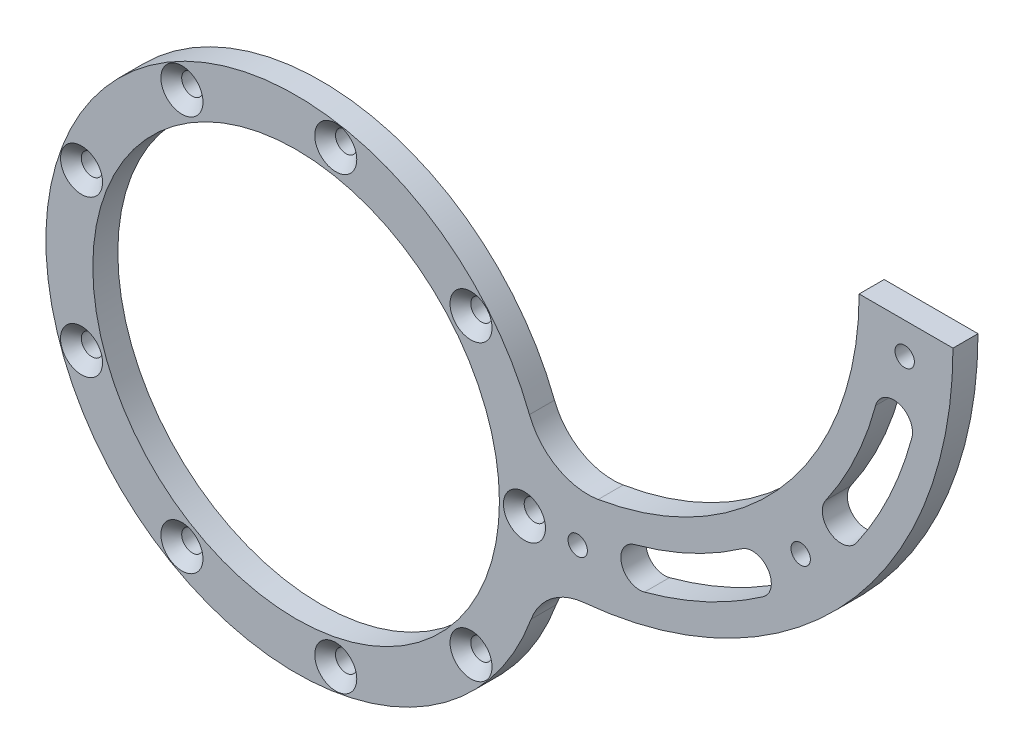
SolidWorks part; units mm, degrees
material "Thornel Mat VMA"
ref_plane "前视基准面" through (0, 0, 0) normal (0, 0, 1) x (1, 0, 0)
ref_plane "上视基准面" through (0, 0, 0) normal (0, 1, 0) x (1, 0, 0)
ref_plane "右视基准面" through (0, 0, 0) normal (1, 0, 0) x (0, 0, -1)
other "Configuration Table"
sketch "草图1" plane through (0, 0, 0) normal (0, 0, 1) x (1, 0, 0)
  circle A0 centre (0, 0) radius 40
  circle A10 centre (0, 0) radius 32.5
  point P3 (0, 0.4883)
  dimension "D1" = 80
  dimension "D6" = 65
extrude "凸台-拉伸1" add sketch "草图1" along normal blind 4
sketch "草图2" plane through (0, 0, 4) normal (0, 0, 1) x (1, 0, 0)
  line L0 (0, 0) -> (40, 0) construction
  line L1 (0, 0) -> (36.5, 0) construction
  circle A0 centre (0, 0) radius 40 construction
  point P6 (36.5, 0)
  point P7 (27.9606, -23.4617)
  point P10 (6.3382, -35.9455)
  point P11 (-18.25, -31.6099)
  point P12 (-34.2988, -12.4837)
  point P13 (-34.2988, 12.4837)
  point P14 (-18.25, 31.6099)
  point P15 (6.3382, 35.9455)
  point P16 (27.9606, 23.4617)
  dimension "D3" = 36.5
  dimension "D2" = 9
hole_wizard "M3 六角凹锥坑螺钉的锥形沉头孔1" positions "草图2" profile "草图3" countersink size "M3" standard "ISO" end condition through all
sketch "草图3" plane through (27.9606, 23.4617, 4) normal (1, 0, 0) x (0, -1, 0)
  line L0 (0, 0) -> (0, 4)
  line L1 (0, 4) -> (1.7, 4)
  line L2 (1.7, 4) -> (1.7, 1.66)
  line L3 (1.7, 1.66) -> (3.36, 0)
  line L5 (3.36, 0) -> (0, 0)
  line L6 (-1.7, 1.66) -> (-3.36, 0) construction
  line L11 (0, -6.35) -> (0, 107.95) construction
  dimension "通孔孔直径" = 3.4
  dimension "通孔孔深度" = 4
  dimension "近端锥形沉头孔直径" = 6.72
  dimension "近端锥形沉头孔角度" = 90
sketch "草图4" plane through (0, 0, 4) normal (0, 0, 1) x (1, 0, 0)
  line L0 (0, 0) -> (40, 0) construction
  line L1 (40, 0) -> (40, 57.5) construction
  line L2 (40, 57.5) -> (97.5, 57.5) construction
  line L3 (45.0115, 0.2188) -> (40, 57.5) construction
  line L4 (40, 57.5) -> (97.2812, 52.4885) construction
  line L5 (80.6586, 16.8414) -> (40, 57.5) construction
  line L6 (92.1127, 33.1994) -> (40, 57.5) construction
  line L7 (90, 57.5) -> (105, 57.5)
  line L14 (40, 57.5) -> (64.3006, 5.3873) construction
  circle A0 centre (0, 0) radius 40 construction
  arc A5 (40, 0) -> (97.5, 57.5) centre (40, 57.5) ccw construction
  arc A18 (90, 57.5) -> (39.2896, 7.505) centre (40, 57.5) cw
  circle A26 centre (45.0115, 0.2188) radius 1.55
  circle A27 centre (80.6586, 16.8414) radius 1.55
  circle A28 centre (97.2812, 52.4885) radius 1.55
  arc A29 (54.9043, 1.9652) -> (72.9618, 10.3856) centre (40, 57.5) ccw construction
  arc A30 (55.6819, -0.9322) -> (74.6816, 7.9274) centre (40, 57.5) ccw
  arc A31 (54.1267, 4.8627) -> (71.2421, 12.8437) centre (40, 57.5) ccw
  arc A32 (54.1267, 4.8627) -> (55.6819, -0.9322) centre (54.9043, 1.9652) ccw
  arc A33 (74.6816, 7.9274) -> (71.2421, 12.8437) centre (72.9618, 10.3856) ccw
  arc A34 (87.1144, 24.5382) -> (95.5348, 42.5957) centre (40, 57.5) ccw construction
  arc A35 (89.5726, 22.8184) -> (98.4322, 41.8181) centre (40, 57.5) ccw
  arc A36 (84.6563, 26.2579) -> (92.6373, 43.3733) centre (40, 57.5) ccw
  arc A37 (84.6563, 26.2579) -> (89.5726, 22.8184) centre (87.1144, 24.5382) ccw
  arc A38 (98.4322, 41.8181) -> (92.6373, 43.3733) centre (95.5348, 42.5957) ccw
  arc A41 (105, 57.5) -> (39.2913, -7.4961) centre (40, 57.5) cw
  arc A42 (39.2896, 7.505) -> (39.2913, -7.4961) centre (0, 0) cw
  point P15 (64.3006, 5.3873)
  point P20 (92.1127, 33.1994)
  dimension "D2" = 50
  dimension "D8" = 3.1
  dimension "D9" = 3.1
  dimension "D10" = 3
  dimension "D15" = 25
  dimension "D16" = 25
  dimension "D6" = 3.1
  dimension "D11" = 3
  dimension "D3" = 65
  dimension "D4" = 57.5
  dimension "D5" = 57.5
  dimension "D7" = 5
  dimension "D12" = 10
  dimension "D13" = 10
  dimension "D14" = 5
  dimension "D17" = 45
extrude "凸台-拉伸2" add sketch "草图4" against normal up to surface (4 mm away) up to face at (38.2, 0, 0)
fillet "圆角1" radius 10 2 edges at (39.2913, -7.4961, 2) (39.2896, 7.505, 2)
